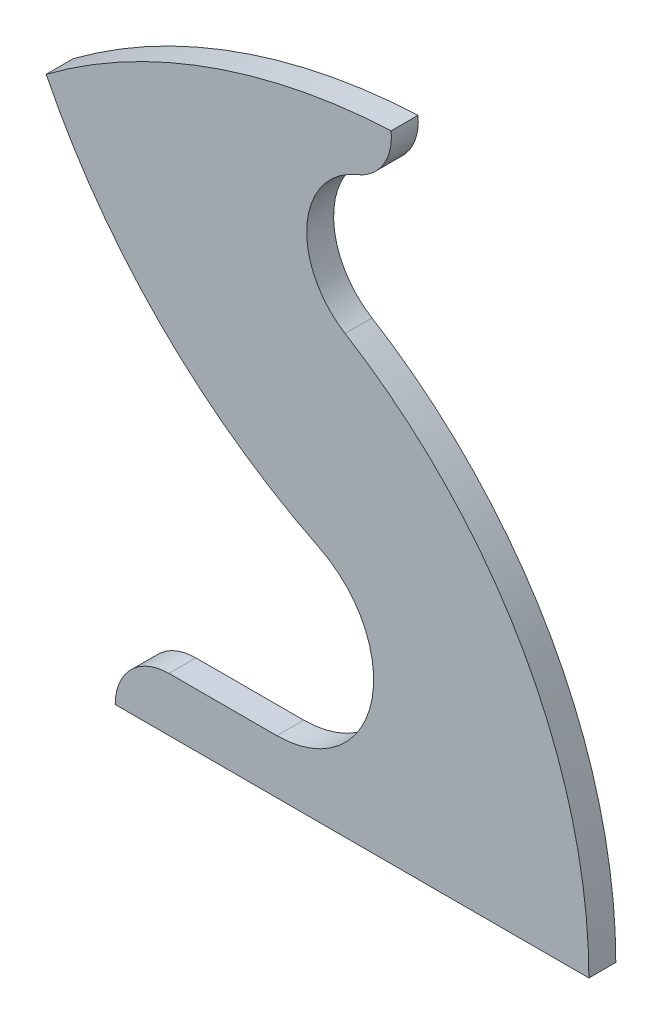
SolidWorks part; units mm, degrees
ref_plane "Front Plane" through (0, 0, 0) normal (0, 0, 1) x (1, 0, 0)
ref_plane "Top Plane" through (0, 0, 0) normal (0, 1, 0) x (1, 0, 0)
ref_plane "Right Plane" through (0, 0, 0) normal (1, 0, 0) x (0, 0, -1)
sketch "Sketch1" plane through (0, 0, 0) normal (0, 0, 1) x (1, 0, 0)
  line L0 (0, 0) -> (0, 62.6107) construction
  line L1 (0, 0) -> (0, -28) construction
  line L2 (0, -28) -> (-20.0164, -28) construction
  line L3 (0, -28) -> (50, -28) construction
  line L4 (-20.0164, -28) -> (-30.0164, -28) construction
  line L5 (-20.0164, -28) -> (-20.0164, -18) construction
  line L6 (-30.0164, -28) -> (57.9836, -28)
  line L7 (57.9836, -28) -> (57.9836, 127.746) construction
  line L8 (57.9836, -28) -> (0, 29.9836) construction
  line L9 (-20.0164, -18) -> (0, -18)
  line L10 (14.9971, 79.753) -> (11.2917, 89.0412) construction
  arc A0 (0, -18) -> (7.9977, 16.1257) centre (0, 0) ccw
  arc A1 (-20.0164, -18) -> (-30.0164, -28) centre (-20.0164, -28) ccw
  arc A4 (57.9836, -28) -> (12.6941, 53.0457) centre (-37.1769, -28) ccw
  arc A6 (52.2407, 4.5576) -> (57.9836, 4.4109) centre (57.9836, 116.9113) ccw
  arc A7 (14.9971, 79.753) -> (12.6941, 53.0457) centre (20.5552, 65.8208) ccw
  arc A8 (14.9971, 79.753) -> (21.2521, 89.9305) centre (11.2917, 89.0412) ccw
  arc A9 (-42.8351, 66.9921) -> (7.9977, 16.1257) centre (57.9836, 116.9113) ccw
  arc A10 (21.2521, 89.9305) -> (-42.8351, 66.9921) centre (26.5789, -25.9471) ccw
  dimension "D1" = 45
extrude "Boss-Extrude1" add sketch "Sketch1" along normal blind 5 contours A8 A10 A9 A0 L9 A1 L6 A4 A7
